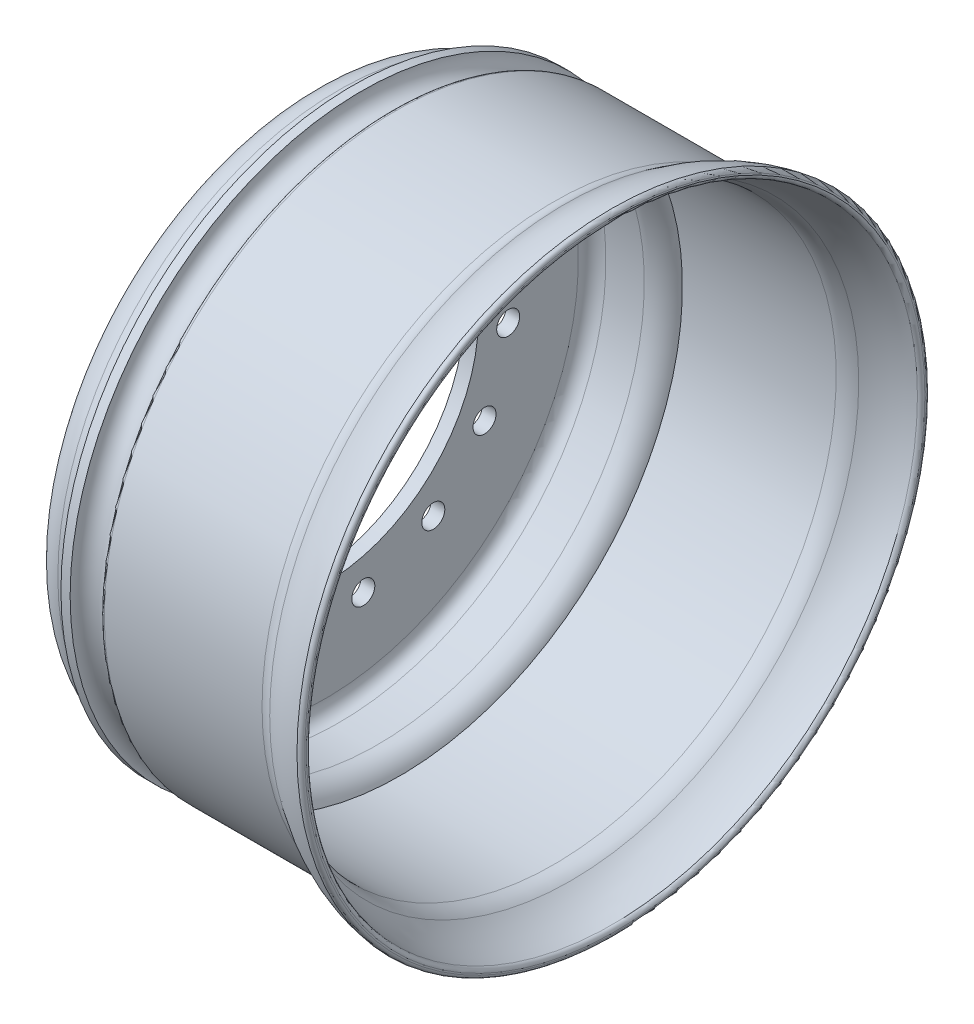
SolidWorks part; units mm, degrees
ref_plane "Front Plane" through (0, 0, 0) normal (0, 0, 1) x (1, 0, 0)
ref_plane "Top Plane" through (0, 0, 0) normal (0, 1, 0) x (1, 0, 0)
ref_plane "Right Plane" through (0, 0, 0) normal (1, 0, 0) x (0, 0, -1)
sketch "Sketch1" plane through (0, 0, 0) normal (0, 0, 1) x (1, 0, 0)
  line L0 (0, 0) -> (34.4361, 0) construction
  line L1 (26, 190) -> (131, 190)
  line L2 (0, 190) -> (6, 190)
  line L3 (0, 184) -> (1.1676, 184)
  line L4 (30.8324, 184) -> (131, 184)
  line L5 (171.5695, 198.9874) -> (171, 204.9603)
  line L6 (16, 174) -> (-9, 174)
  line L7 (-18, 165) -> (-18, 100)
  line L8 (-18, 100) -> (-27, 100)
  line L9 (-27, 100) -> (-27, 165)
  line L10 (-9, 183) -> (1.6125, 183)
  line L11 (0, 184) -> (0, 190)
  arc A0 (6, 190) -> (26, 190) centre (16, 190) ccw
  arc A1 (131, 190) -> (138.4468, 192.4603) centre (131, 202.5) ccw
  arc A2 (138.4468, 192.4603) -> (171, 204.9603) centre (177.1699, 140.2538) cw
  arc A3 (1.1676, 184) -> (1.6125, 183) centre (16, 190) ccw
  arc A4 (131, 184) -> (142.0212, 187.6412) centre (131, 202.5) ccw
  arc A5 (142.0212, 187.6412) -> (171.5695, 198.9874) centre (177.1699, 140.2538) cw
  arc A6 (-9, 174) -> (-18, 165) centre (-9, 165) ccw
  arc A7 (-27, 165) -> (-9, 183) centre (-9, 165) cw
  arc A8 (16, 174) -> (30.8324, 184) centre (16, 190) ccw
  arc A10 (1.1676, 184) -> (30.8324, 184) centre (16, 190) ccw construction
  dimension "D2" = 10
  dimension "D4" = 12.5
  dimension "D5" = 65
  dimension "D10" = 9
  dimension "D11" = 18
  dimension "D14" = 9
  dimension "D1" = 6
  dimension "D3" = 105
  dimension "D6" = 12.5
  dimension "D7" = 145
  dimension "D8" = 190
  dimension "D12" = 9
  dimension "D13" = 65
  dimension "D15" = 25
  dimension "D9" = 6
revolve "Revolve1" add sketch "Sketch1" angle 360 about L0
sketch "Sketch2" plane through (-27, 0, 0) normal (-1, 0, 0) x (0, 0, 1)
  circle A0 centre (0, 120) radius 7.5
  dimension "D1" = 15
  dimension "D2" = 120
extrude "Cut-Extrude1" cut sketch "Sketch2" against normal through all
pattern_circular "CirPattern1" count 15 over 360 about axis through (0, 0, 0) along (1, 0, 0) of "Cut-Extrude1"
fillet "Fillet1" radius 2.5 2 edges at (171.5695, 0, 198.9874) (171, 0, 204.9603)
fillet "Fillet3" radius 2.5 1 edges at (26, 0, 190)
